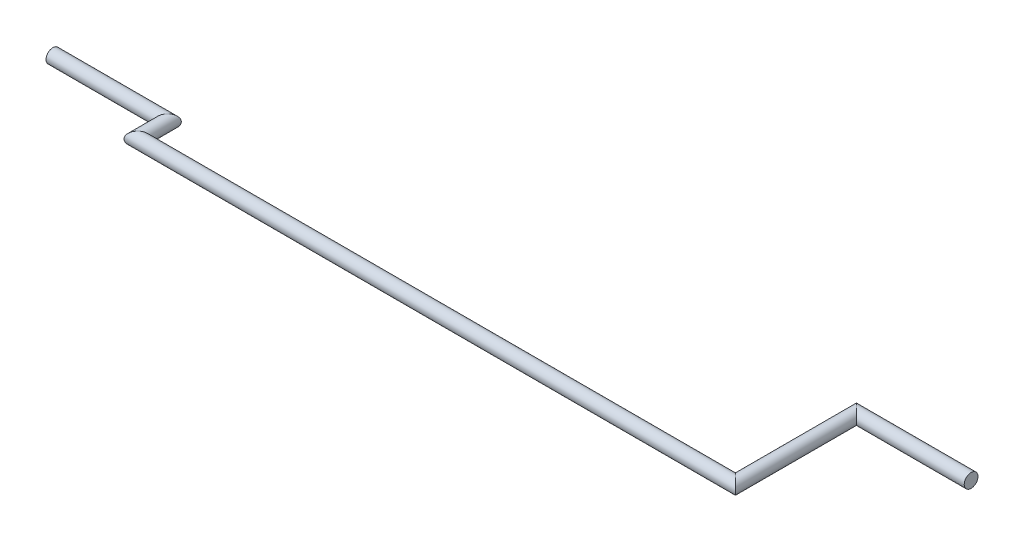
SolidWorks part; units mm, degrees
ref_plane "Front Plane" through (0, 0, 0) normal (0, 0, 1) x (1, 0, 0)
ref_plane "Top Plane" through (0, 0, 0) normal (0, 1, 0) x (1, 0, 0)
ref_plane "Right Plane" through (0, 0, 0) normal (1, 0, 0) x (0, 0, -1)
sketch "Sketch1" plane through (0, 0, 0) normal (0, 1, 0) x (1, 0, 0)
  line L0 (0, 0) -> (52.11, 0)
  line L1 (52.11, 0) -> (52.11, 10.55)
  line L2 (52.11, 10.55) -> (62.11, 10.55)
  line L3 (0, 0) -> (0, 2.6)
  line L4 (0, 2.6) -> (-10, 2.6)
  dimension "D1" = 10.55
  dimension "D2" = 2.6
  dimension "D3" = 10
  dimension "D4" = 10
  dimension "D5" = 52.11
sweep "Sweep1" add path "Sketch1" circular profile diameter 1.2 parameters "D3"=1.2
